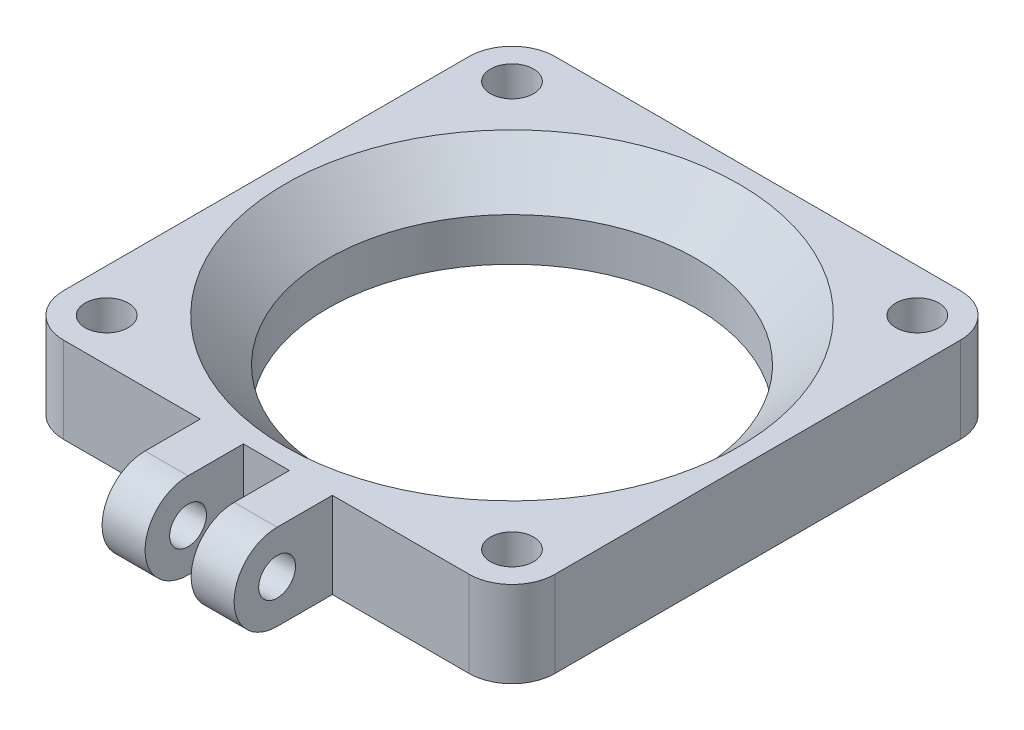
SolidWorks part; units mm, degrees
ref_plane "Front Plane" through (0, 0, 0) normal (0, 0, 1) x (1, 0, 0)
ref_plane "Top Plane" through (0, 0, 0) normal (0, 1, 0) x (1, 0, 0)
ref_plane "Right Plane" through (0, 0, 0) normal (1, 0, 0) x (0, 0, -1)
sketch "Sketch1" plane through (0, 0, 0) normal (0, 1, 0) x (1, 0, 0)
  line L1 (-16.5, 20) -> (16.5, 20)
  line L2 (-20, 16.5) -> (-20, -16.5)
  line L3 (-16.5, -20) -> (16.5, -20)
  line L4 (20, 16.5) -> (20, -16.5)
  line L5 (-20, 20) -> (20, -20) construction
  line L6 (-20, -20) -> (20, 20) construction
  arc A0 (-20, -16.5) -> (-16.5, -20) centre (-16.5, -16.5) ccw
  arc A1 (16.5, -20) -> (20, -16.5) centre (16.5, -16.5) ccw
  arc A2 (16.5, 20) -> (20, 16.5) centre (16.5, 16.5) cw
  arc A3 (-16.5, 20) -> (-20, 16.5) centre (-16.5, 16.5) ccw
  point P0 (0, 0)
  dimension "D1" = 3.5
  dimension "D2" = 40
  dimension "D3" = 40
extrude "Boss-Extrude1" add sketch "Sketch1" along normal blind 7
sketch "Sketch3" plane through (0, 7, 0) normal (0, 1, 0) x (1, 0, 0)
  line L0 (0, 20) -> (0, -20) construction
  line L1 (16.5, 20) -> (-16.5, 20) construction
  line L2 (-16.5, -20) -> (16.5, -20) construction
  line L3 (-20, 0) -> (20, 0) construction
  line L4 (-20, 16.5) -> (-20, -16.5) construction
  line L5 (20, -16.5) -> (20, 16.5) construction
  circle A1 centre (-16.5, 16.5) radius 1.75
  circle A2 centre (16.5, 16.5) radius 1.75
  circle A3 centre (16.5, -16.5) radius 1.75
  circle A4 centre (-16.5, -16.5) radius 1.75
  dimension "D1" = 3.5
extrude "Cut-Extrude2" cut sketch "Sketch3" against normal up to next
sketch "Sketch7" plane through (0, 0, 0) normal (0, -1, 0) x (1, 0, 0)
  line L0 (0, 0) -> (0, 20) construction
  line L1 (-16.5, 20) -> (16.5, 20) construction
  line L2 (-20, 0) -> (20, 0) construction
  line L3 (-20, -16.5) -> (-20, 16.5) construction
  line L4 (20, 16.5) -> (20, -16.5) construction
  line L5 (5.375, 0) -> (5.375, 28)
  line L6 (-1.875, 0) -> (-5.375, 0)
  line L7 (-1.875, 0) -> (-1.875, 28)
  line L8 (-1.875, 28) -> (-5.375, 28)
  line L9 (-5.375, 0) -> (-5.375, 28)
  line L10 (1.875, 28) -> (5.375, 28)
  line L11 (1.875, 0) -> (1.875, 28)
  line L12 (1.875, 0) -> (5.375, 0)
  dimension "D1" = 3.5
  dimension "D2" = 8
  dimension "D3" = 3.75
extrude "Boss-Extrude2" add sketch "Sketch7" against normal blind 7
sketch "Sketch8" plane through (5.375, 0, 0) normal (1, 0, 0) x (0, 0, -1)
  line L0 (-20, 7) -> (-28, 7) construction
  line L1 (-20, 0) -> (-28, 0) construction
  line L2 (-28, 7) -> (-28, 0) construction
  line L3 (-24.5, 7) -> (-28, 7)
  line L4 (-28, 7) -> (-28, 3.5)
  line L5 (-28, 3.5) -> (-28, 0)
  line L6 (-28, 0) -> (-24.5, 0)
  arc A0 (-24.5, 7) -> (-24.5, 0) centre (-24.5, 3.5) ccw
  line M4 (-20, 7) -> (-28, 7)
  line M5 (-28, 7) -> (-28, 0)
  line M6 (-28, 0) -> (-20, 0)
extrude "Cut-Extrude3" cut sketch "Sketch8" against normal through all contours A0 M4 M5 | A0 M5 M6
sketch "Sketch9" plane through (5.375, 0, 0) normal (1, 0, 0) x (0, 0, -1)
  circle A0 centre (-24.5, 3.5) radius 1.5
  dimension "D1" = 3
extrude "Cut-Extrude4" cut sketch "Sketch9" against normal through all
sketch "Sketch13" plane through (0, 0, 0) normal (0, -1, 0) x (1, 0, 0)
  line L0 (-20, 0) -> (20, 0) construction
  line L1 (-20, -16.5) -> (-20, 16.5) construction
  line L2 (20, 16.5) -> (20, -16.5) construction
  line L3 (0, -20) -> (0, 20) construction
  line L4 (16.5, -20) -> (-16.5, -20) construction
  line L5 (-1.875, 20) -> (1.875, 20) construction
  circle A0 centre (0, 0) radius 15
  dimension "D1" = 30
extrude "Cut-Extrude5" cut sketch "Sketch13" against normal through all
ref_axis "Axis3" through (0, 7, 0) along (0, -1, 0)
ref_plane "Plane2" through (0, 0, 0) normal (1, 0, 0) x (0, 0, -1)
sketch "Sketch14" plane through (0, 0, 0) normal (1, 0, 0) x (0, 0, -1)
  line L0 (0, 0) -> (0, 7)
  line L1 (0, 7) -> (0, 0) construction
  line L2 (0, 7) -> (18.5, 7)
  line L3 (-16.5, 7) -> (16.5, 7) construction
  line L4 (18.5, 7) -> (15, 3.5)
  line L5 (15, 3.5) -> (15, 0)
  line L6 (-16.5, 0) -> (16.5, 0) construction
  line L7 (15, 0) -> (0, 0)
  line L8 (-15, 0) -> (15, 0) construction
  line L9 (15, 7) -> (-15, 7) construction
  point P16 (15, 0)
  dimension "D1" = 3.5
  dimension "D2" = 45
revolve "Cut-Revolve1" cut sketch "Sketch14" angle 360 about axis through (0, 7, 0) along (0, -1, 0)
move or copy body "Body-Move/Copy1" [suppressed] bodies to move or copy 112 copy no rotation origin (0, 3.5, 4) rotation axis (1, 0, 0) rotation angle 90
